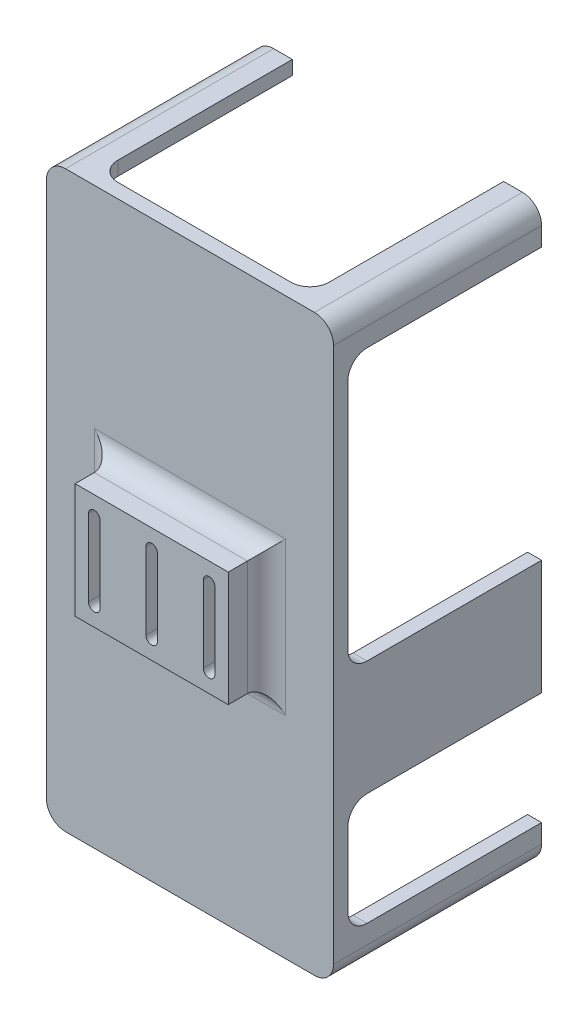
SolidWorks part; units mm, degrees
ref_plane "Front Plane" through (0, 0, 0) normal (0, 0, 1) x (1, 0, 0)
ref_plane "Top Plane" through (0, 0, 0) normal (0, 1, 0) x (1, 0, 0)
ref_plane "Right Plane" through (0, 0, 0) normal (1, 0, 0) x (0, 0, -1)
sketch "Sketch2" plane through (0, 0, 0) normal (0, 0, 1) x (1, 0, 0)
  line L1 (65.612, -435) -> (-84.388, -435)
  line L2 (65.612, -435) -> (65.612, -135)
  line L3 (65.612, -135) -> (-84.388, -135)
  line L4 (-84.388, -435) -> (-84.388, -135)
  line L6 (58.112, -427.5) -> (58.112, -142.5) construction
  line L8 (48.112, -427.5) -> (-66.888, -427.5) construction
  dimension "D1" = 150
  dimension "D2" = 300
  dimension "D3" = 7.5
  dimension "D4" = 7.5
extrude "BoxPlatform" add sketch "Sketch2" along normal blind 7.5
sketch "Sketch3" plane through (0, 0, 7.5) normal (0, 0, 1) x (1, 0, 0)
  line L7 (-49.388, -315) -> (-49.388, -255)
  line L8 (30.612, -315) -> (30.612, -255)
  line L9 (30.612, -255) -> (-49.388, -255)
  line L10 (-49.388, -315) -> (30.612, -315)
  line L13 (-84.388, -435) -> (65.612, -435) construction
  line L14 (65.612, -435) -> (65.612, -135) construction
  dimension "D1" = 60
  dimension "D2" = 80
  dimension "D3" = 35
  dimension "D4" = 120
extrude "ExtrusionConnection" add sketch "Sketch3" along normal blind 20
fillet "Fillet1" radius 10 4 edges at (30.612, -285, 7.5) (-9.388, -315, 7.5) (-49.388, -285, 7.5) (-9.388, -255, 7.5)
sketch "Sketch5" plane through (0, 0, 27.5) normal (0, 0, 1) x (1, 0, 0)
  line L0 (20.612, -305) -> (20.612, -265) construction
  line L1 (17.612, -305) -> (17.612, -265)
  line L2 (23.612, -305) -> (23.612, -265)
  line L3 (-39.388, -305) -> (-39.388, -265) construction
  line L4 (-42.388, -305) -> (-42.388, -265)
  line L5 (-36.388, -305) -> (-36.388, -265)
  line L6 (-9.388, -305) -> (-9.388, -265) construction
  line L9 (-84.388, -135) -> (-84.388, -435) construction
  line L10 (-12.388, -305) -> (-12.388, -265)
  line L11 (-6.388, -305) -> (-6.388, -265)
  line L13 (65.612, -435) -> (65.612, -135) construction
  line L17 (65.612, -135) -> (-84.388, -135) construction
  arc A0 (17.612, -305) -> (23.612, -305) centre (20.612, -305) ccw
  arc A1 (23.612, -265) -> (17.612, -265) centre (20.612, -265) ccw
  arc A2 (-42.388, -305) -> (-36.388, -305) centre (-39.388, -305) ccw
  arc A3 (-36.388, -265) -> (-42.388, -265) centre (-39.388, -265) ccw
  arc A6 (-12.388, -305) -> (-6.388, -305) centre (-9.388, -305) ccw
  arc A7 (-6.388, -265) -> (-12.388, -265) centre (-9.388, -265) ccw
  point P2 (20.612, -285)
  point P7 (-39.388, -285)
  point P16 (-9.388, -285)
  dimension "D10" = 150
  dimension "D1" = 6
  dimension "D2" = 45
  dimension "D3" = 6
  dimension "D4" = 45
  dimension "D5" = 75
  dimension "D6" = 6
  dimension "D7" = 40
  dimension "D8" = 40
  dimension "D9" = 40
  dimension "D11" = 150
  dimension "D12" = 150
extrude "MountSlots" cut sketch "Sketch5" against normal through all
sketch "Sketch6" plane through (0, 0, 0) normal (0, 0, -1) x (-1, 0, 0)
  line L0 (-20.612, -265) -> (-20.612, -305) construction
  line L1 (-15.612, -265) -> (-15.612, -305)
  line L2 (-25.612, -265) -> (-25.612, -305)
  line L3 (9.388, -265) -> (9.388, -305) construction
  line L4 (14.388, -265) -> (14.388, -305)
  line L5 (4.388, -265) -> (4.388, -305)
  line L6 (39.388, -265) -> (39.388, -305) construction
  line L7 (44.388, -265) -> (44.388, -305)
  line L8 (34.388, -265) -> (34.388, -305)
  arc A0 (-15.612, -265) -> (-25.612, -265) centre (-20.612, -265) ccw
  arc A1 (-25.612, -305) -> (-15.612, -305) centre (-20.612, -305) ccw
  arc A2 (14.388, -265) -> (4.388, -265) centre (9.388, -265) ccw
  arc A3 (4.388, -305) -> (14.388, -305) centre (9.388, -305) ccw
  arc A4 (44.388, -265) -> (34.388, -265) centre (39.388, -265) ccw
  arc A5 (34.388, -305) -> (44.388, -305) centre (39.388, -305) ccw
  point P4 (-20.612, -285)
  point P9 (9.388, -285)
  point P18 (39.388, -285)
  dimension "D1" = 10
  dimension "D2" = 10
  dimension "D3" = 10
extrude "WasherSlots" cut sketch "Sketch6" against normal blind 20
sketch "Sketch7" plane through (0, 0, 0) normal (0, 0, -1) x (-1, 0, 0)
  line L0 (64.588, -135) -> (84.388, -135)
  line L1 (-65.612, -135) -> (84.388, -135) construction
  line L2 (84.388, -135) -> (84.388, -154.8)
  line L3 (84.388, -135) -> (84.388, -435) construction
  line L4 (84.388, -154.8) -> (77.088, -154.8)
  line L5 (77.088, -154.8) -> (77.088, -142.3)
  line L6 (77.088, -142.3) -> (64.588, -142.3)
  line L7 (64.588, -142.3) -> (64.588, -135)
  line L8 (84.388, -435) -> (84.388, -415.2)
  line L9 (84.388, -415.2) -> (77.088, -415.2)
  line L10 (77.088, -415.2) -> (77.088, -427.7)
  line L11 (77.088, -427.7) -> (64.588, -427.7)
  line L12 (64.588, -427.7) -> (64.588, -435)
  line L13 (84.388, -435) -> (-65.612, -435) construction
  line L14 (64.588, -435) -> (84.388, -435)
  line L15 (-45.812, -142.3) -> (-58.312, -142.3)
  line L16 (-58.312, -142.3) -> (-58.312, -154.8)
  line L17 (-65.612, -435) -> (-65.612, -415.2)
  line L18 (-65.612, -435) -> (-65.612, -135) construction
  line L19 (-65.612, -415.2) -> (-58.312, -415.2)
  line L20 (-58.312, -415.2) -> (-58.312, -427.7)
  line L21 (-58.312, -427.7) -> (-45.812, -427.7)
  line L22 (-45.812, -427.7) -> (-45.812, -435)
  line L23 (-45.812, -435) -> (-65.612, -435)
  line L24 (-65.612, -135) -> (-45.812, -135)
  line L25 (-45.812, -135) -> (-45.812, -142.3)
  line L26 (-58.312, -154.8) -> (-65.612, -154.8)
  line L27 (-65.612, -154.8) -> (-65.612, -135)
  line L28 (-35.612, -361.5) -> (-40.612, -361.5) construction
  line L29 (-65.612, -296.5) -> (-58.312, -296.5)
  line L30 (-65.612, -296.5) -> (-65.612, -356.5)
  line L31 (-65.612, -356.5) -> (-58.312, -356.5)
  line L32 (-58.312, -296.5) -> (-58.312, -356.5)
  line L33 (-58.112, -427.5) -> (-58.112, -142.5) construction
  line L34 (-48.112, -427.5) -> (66.888, -427.5) construction
  line L35 (76.888, -142.5) -> (76.888, -427.5) construction
  line L36 (66.888, -142.5) -> (-48.112, -142.5) construction
  line L37 (76.888, -427.5) -> (76.888, -283) construction
  line L38 (84.388, -296.5) -> (77.088, -296.5)
  line L39 (84.388, -296.5) -> (84.388, -356.5)
  line L40 (84.388, -356.5) -> (77.088, -356.5)
  line L41 (77.088, -296.5) -> (77.088, -356.5)
  point P40 (-61.962, -356.5)
  dimension "D1" = 60
  dimension "D2" = 5
  dimension "D3" = 0.2
  dimension "D4" = 0.2
  dimension "D5" = 0.2
  dimension "D6" = 0.2
  dimension "D7" = 0.2
  dimension "D8" = 0.2
  dimension "D9" = 0.2
  dimension "D10" = 0.2
  dimension "D11" = 0.2
  dimension "D12" = 0.2
  dimension "D13" = 60
  dimension "D14" = 12.5
extrude "Walls" add sketch "Sketch7" along normal blind 101.2
fillet "Fillet2" radius 10 4 edges at (-84.388, -435, -46.85) (65.612, -435, -46.85) (65.612, -135, -46.85) (-84.388, -135, -46.85)
fillet "Fillet3" radius 10 12 edges at (45.812, -138.65, 0) (-64.588, -138.65, 0) (61.962, -154.8, 0) (61.962, -296.5, 0) (61.962, -356.5, 0) (61.962, -415.2, 0) (45.812, -431.35, 0) (-64.588, -431.35, 0) (-80.738, -415.2, 0) (-80.738, -356.5, 0) (-80.738, -154.8, 0) (-80.738, -296.5, 0)
sketch "Sketch8" plane through (0, 0, -101.2) normal (0, 0, -1) x (-1, 0, 0)
  line L1 (84.388, -154.8) -> (84.388, -145) construction
  line L2 (77.088, -154.8) -> (84.388, -154.8) construction
  line L3 (84.388, -296.5) -> (77.088, -296.5) construction
  line L4 (84.388, -415.2) -> (77.088, -415.2) construction
  line L5 (-58.312, -154.8) -> (-58.312, -142.3) construction
  circle A0 centre (80.888, -147.8) radius 2
  circle A1 centre (-61.812, -147.8) radius 2
  circle A2 centre (80.888, -326.5) radius 2
  circle A3 centre (-61.812, -326.5) radius 2
  circle A4 centre (80.888, -422.2) radius 2
  circle A5 centre (-61.812, -422.2) radius 2
  dimension "D1" = 4
  dimension "D2" = 3.5
  dimension "D3" = 7
  dimension "D4" = 30
  dimension "D5" = 7
  dimension "D6" = 3.5
extrude "M3x7mmHoles" cut sketch "Sketch8" against normal blind 8
